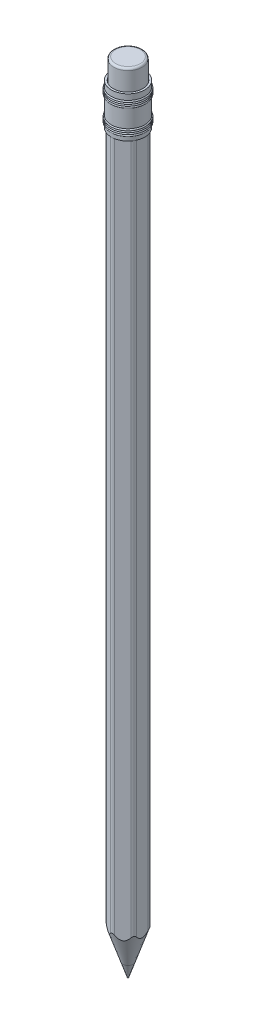
SolidWorks part; units mm, degrees
ref_plane "Front" through (0, 0, 0) normal (0, 0, 1) x (1, 0, 0)
ref_plane "Top" through (0, 0, 0) normal (0, 1, 0) x (1, 0, 0)
ref_plane "Right" through (0, 0, 0) normal (1, 0, 0) x (0, 0, -1)
sketch "Sketch1" plane through (0, 0, 0) normal (0, 1, 0) x (1, 0, 0)
  circle A0 centre (0, 0) radius 1.25
  dimension "D1" = 2.5
extrude "Lead" add sketch "Sketch1" along normal blind 185
sketch "Sketch2" plane through (0, 0, 0) normal (0, -1, 0) x (1, 0, 0)
  line L1 (0, 4.0415) -> (-3.5, 2.0207)
  line L2 (-3.5, 2.0207) -> (-3.5, -2.0207)
  line L3 (-3.5, -2.0207) -> (0, -4.0415)
  line L4 (0, -4.0415) -> (3.5, -2.0207)
  line L5 (3.5, -2.0207) -> (3.5, 2.0207)
  line L6 (3.5, 2.0207) -> (0, 4.0415)
  circle A0 centre (0, 0) radius 3.5 construction
  circle A1 centre (0, 0) radius 1.25
  circle A2 centre (0, 0) radius 1.25 construction
  dimension "D1" = 7
extrude "Casing" add sketch "Sketch2" against normal up to surface (185 mm away) separate body up to face at (0, 185, 1.25)
sketch "Sketch3" plane through (0, 185, 0) normal (0, 1, 0) x (1, 0, 0)
  circle A0 centre (0, 0) radius 3.5
  dimension "D1" = 7
extrude "Eraser" add sketch "Sketch3" along normal blind 10 separate body
sketch "Sketch4" plane through (0, 0, 0) normal (1, 0, 0) x (0, 0, -1)
  line L0 (0, 185) -> (0, 195) construction
  line L1 (-3.5, 185) -> (3.5, 185) construction
  line L2 (3.5, 195) -> (-3.5, 195) construction
  line L3 (-3.6, 180) -> (-4.1, 180)
  line L4 (-4.1, 180) -> (-4.1, 190) construction
  line L5 (-4.1, 190) -> (-3.6, 190)
  line L6 (-4.1, 180) -> (-4.1, 181)
  line L7 (-4.0415, 185) -> (-2.0207, 185) construction
  line L8 (-4.1, 182.6) -> (-4.1, 187)
  line L9 (-3.6, 188.6) -> (-3.6, 190)
  line L10 (-4.1, 188.6) -> (-4.1, 190)
  line L11 (-3.85, 190) -> (-3.85, 180) construction
  line L12 (-3.6, 180) -> (-3.6, 181)
  line L13 (-3.6, 182.6) -> (-3.6, 187)
  arc A0 (-4.1, 181) -> (-4.1, 181.4) centre (-4.1, 181.2) cw
  arc A1 (-4.1, 181.4) -> (-4.1, 181.8) centre (-4.1, 181.6) cw
  arc A2 (-4.1, 181.8) -> (-4.1, 182.2) centre (-4.1, 182) cw
  arc A3 (-4.1, 182.2) -> (-4.1, 182.6) centre (-4.1, 182.4) cw
  arc A4 (-4.1, 187) -> (-4.1, 187.4) centre (-4.1, 187.2) cw
  arc A5 (-4.1, 187.4) -> (-4.1, 187.8) centre (-4.1, 187.6) cw
  arc A6 (-4.1, 187.8) -> (-4.1, 188.2) centre (-4.1, 188) cw
  arc A7 (-4.1, 188.2) -> (-4.1, 188.6) centre (-4.1, 188.4) cw
  arc A8 (-3.6, 188.2) -> (-3.6, 188.6) centre (-3.6, 188.4) ccw
  arc A9 (-3.6, 187.8) -> (-3.6, 188.2) centre (-3.6, 188) ccw
  arc A10 (-3.6, 187.4) -> (-3.6, 187.8) centre (-3.6, 187.6) ccw
  arc A11 (-3.6, 187) -> (-3.6, 187.4) centre (-3.6, 187.2) ccw
  arc A12 (-3.6, 182.2) -> (-3.6, 182.6) centre (-3.6, 182.4) ccw
  arc A13 (-3.6, 181.8) -> (-3.6, 182.2) centre (-3.6, 182) ccw
  arc A14 (-3.6, 181.4) -> (-3.6, 181.8) centre (-3.6, 181.6) ccw
  arc A15 (-3.6, 181) -> (-3.6, 181.4) centre (-3.6, 181.2) ccw
  dimension "D5" = 1
  dimension "D6" = 0.2
  dimension "D1" = 3.6
  dimension "D2" = 0.5
  dimension "D3" = 5
  dimension "D4" = 10
  dimension "D7" = 4
  dimension "D8" = 2
revolve "Ferrule Revolve " add sketch "Sketch4" angle 360 about L0
fillet "Fillet1" radius 1 6 edges at (0, 92.5, 4.0415) (-3.5, 92.5, 2.0207) (3.5, 92.5, -2.0207) (3.5, 92.5, 2.0207) (-3.5, 92.5, -2.0207) (0, 92.5, -4.0415)
fillet "Fillet2" radius 0.5 1 edges at (0, 195, 3.5)
sketch "Sketch5" plane through (1.75, 0, -3.0311) normal (0.5, 0, -0.866) x (-0.866, 0, -0.5)
  line L0 (1.2434, 149.9829) -> (1.2434, 179.9829) construction
  line L1 (1.4434, 0) -> (1.4434, 185) construction
  text T0 "Pencil 2B" font "Century Gothic" height in points 9
  dimension "D1" = 0.2
  dimension "D2" = 30
extrude "Text Cut" cut sketch "Sketch5" against normal blind 0.25
sketch "Sketch6" plane through (0, 0, 0) normal (0, 0, 1) x (1, 0, 0)
  line L0 (0, 0) -> (0, 1) construction
  line L1 (-0.1, 0) -> (-4.1, 12)
  line L3 (-4.1, 0) -> (-4.1, 12)
  line L4 (-4.1, 0) -> (-0.1, 0)
  line L8 (-0.5, 0) -> (0.5, 0) construction
  dimension "D1" = 0.1
  dimension "D2" = 4
  dimension "D3" = 12
  dimension "D4" = 1
revolve "Cut-Revolve4" cut sketch "Sketch6" angle 360 about L0
